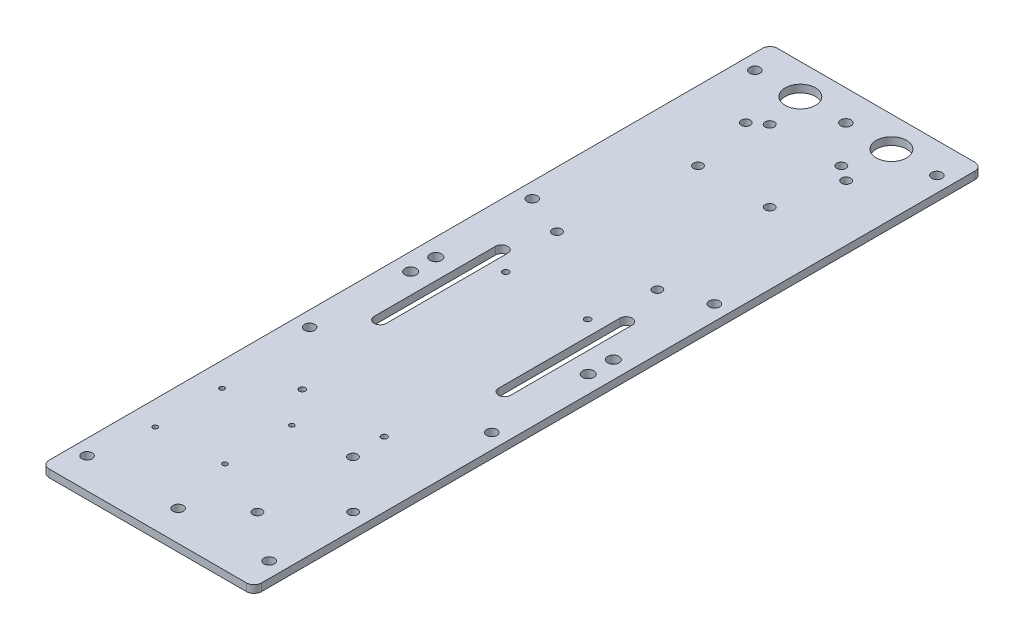
SolidWorks part; units mm, degrees
ref_plane "Front Plane" through (0, 0, 0) normal (0, 0, 1) x (1, 0, 0)
ref_plane "Top Plane" through (0, 0, 0) normal (0, 1, 0) x (1, 0, 0)
ref_plane "Right Plane" through (0, 0, 0) normal (1, 0, 0) x (0, 0, -1)
sketch "Sketch2" plane through (0, 0, 0) normal (0, 1, 0) x (1, 0, 0)
  line L0 (-44.45, 0) -> (44.45, 0) construction
  line L1 (-41.275, 152.4) -> (41.275, 152.4)
  line L2 (-44.45, 149.225) -> (-44.45, -149.225)
  line L3 (-41.275, -152.4) -> (41.275, -152.4)
  line L4 (44.45, 149.225) -> (44.45, -149.225)
  line L5 (0, 152.4) -> (0, -152.4) construction
  arc A0 (-44.45, -149.225) -> (-41.275, -152.4) centre (-41.275, -149.225) ccw
  arc A1 (41.275, -152.4) -> (44.45, -149.225) centre (41.275, -149.225) ccw
  arc A2 (41.275, 152.4) -> (44.45, 149.225) centre (41.275, 149.225) cw
  arc A3 (-41.275, 152.4) -> (-44.45, 149.225) centre (-41.275, 149.225) ccw
  point P8 (0, 0)
  point P13 (-44.45, -152.4)
  point P16 (44.45, -152.4)
  point P21 (-44.45, 152.4)
  dimension "D3" = 3.175
  dimension "D1" = 304.8
  dimension "D2" = 88.9
extrude "Plate Thickness" add sketch "Sketch2" along normal blind 3.175 contours L2 A0 L3 A1 L4 A2 L1 A3
sketch "Sketch3" plane through (0, 3.175, 0) normal (0, 1, 0) x (1, 0, 0)
  line L0 (-44.45, 149.225) -> (-44.45, -149.225) construction
  line L1 (-41.275, 152.4) -> (41.275, 152.4) construction
  line L4 (0, 152.4) -> (0, -152.4) construction
  line L5 (-41.275, -152.4) -> (41.275, -152.4) construction
  line L6 (-41.275, -152.4) -> (41.275, -152.4) construction
  circle A0 centre (-38.1, 139.7) radius 2.159
  circle A1 centre (-38.1, 46.5667) radius 2.159
  circle A2 centre (-38.1, -46.5667) radius 2.159
  circle A3 centre (-38.1, -139.7) radius 2.159
  circle A4 centre (38.1, -139.7) radius 2.159
  circle A5 centre (38.1, -46.5667) radius 2.159
  circle A6 centre (38.1, 46.5667) radius 2.159
  circle A7 centre (38.1, 139.7) radius 2.159
  circle A8 centre (0, 139.7) radius 2.159
  circle A9 centre (0, -139.7) radius 2.159
  dimension "D1" = 4.318
  dimension "D4" = 4.318
  dimension "D2" = 6.35
  dimension "D3" = 12.7
  dimension "D5" = 12.7
  dimension "D6" = 12.7
  dimension "D7" = 93.1333
  dimension "D8" = 93.1333
extrude "Mounting holes" cut sketch "Sketch3" against normal through all
sketch "Sketch4" plane through (0, 3.175, 0) normal (0, 1, 0) x (1, 0, 0)
  line L0 (-21.0058, 39.8143) -> (21.0058, 39.8143) construction
  line L1 (0, 0) -> (0, 139.7) construction
  circle A0 centre (-21.0058, 118.8083) radius 1.905
  circle A1 centre (-21.0058, 39.8143) radius 1.905
  circle A2 centre (21.0058, 39.8143) radius 1.905
  circle A3 centre (21.0058, 118.8083) radius 1.905
  point P13 (0, 39.8143)
  point P17 (0, 69.85)
  point P18 (0, 69.85)
  dimension "D1" = 3.81
  dimension "D2" = 78.994
  dimension "D3" = 42.0116
extrude "Jetson Holes (w/o mount)" cut sketch "Sketch4" against normal through all
sketch "Sketch5" plane through (0, 3.175, 0) normal (0, 1, 0) x (1, 0, 0)
  line L0 (-41.275, 152.4) -> (41.275, 152.4) construction
  line L1 (44.45, 149.225) -> (44.45, -149.225) construction
  circle A1 centre (-15.3784, 123.19) radius 1.905
  circle A3 centre (14.619, 123.19) radius 1.905
  circle A4 centre (14.619, 93.1926) radius 1.905
  circle A5 centre (-15.3784, 93.1926) radius 1.905
  dimension "D1" = 3.81
  dimension "D2" = 29.9974
  dimension "D4" = 29.21
  dimension "D5" = 29.831
  dimension "D3" = 29.9974
extrude "PDB holes" cut sketch "Sketch5" against normal through all
sketch "Sketch6" plane through (0, 3.175, 0) normal (0, 1, 0) x (1, 0, 0)
  line L0 (-41.275, -152.4) -> (41.275, -152.4) construction
  circle A6 centre (37.9175, -104.394) radius 1.905
  circle A7 centre (17.9175, -84.46) radius 1.905
  circle A8 centre (17.9175, -124.46) radius 1.905
  dimension "D1" = 27.94
  dimension "D5" = 3.81
  dimension "D6" = 40
  dimension "D7" = 20
  dimension "D8" = 20.066
sketch "Sketch7" plane through (0, 3.175, 0) normal (0, 1, 0) x (1, 0, 0)
  line L0 (0, 152.4) -> (0, -152.4) construction
  line L1 (-41.275, 152.4) -> (41.275, 152.4) construction
  line L2 (-41.275, -152.4) -> (41.275, -152.4) construction
  line L3 (17.145, 14.4893) -> (-17.145, 14.4893) construction
  circle A0 centre (-17.145, 14.4893) radius 1.27
  circle A1 centre (-17.145, -70.6007) radius 1.27
  circle A2 centre (17.145, -70.6007) radius 1.27
  circle A3 centre (17.145, 14.4893) radius 1.27
  point P14 (0, 14.4893)
  dimension "D1" = 2.54
  dimension "D2" = 85.09
  dimension "D3" = 34.29
extrude "PixHawk Holes" cut sketch "Sketch7" against normal through all
sketch "Sketch8" plane through (0, 3.175, 0) normal (0, 1, 0) x (1, 0, 0)
  line L0 (0, 152.4) -> (0, -115.5095) construction
  line L1 (-41.275, 152.4) -> (41.275, 152.4) construction
  line L2 (-26.035, 21.6897) -> (-26.035, -29.1103) construction
  line L3 (-23.495, 21.6897) -> (-23.495, -29.1103)
  line L4 (-28.575, 21.6897) -> (-28.575, -29.1103)
  line L5 (26.035, 21.6897) -> (26.035, -29.1103) construction
  line L6 (23.495, 21.6897) -> (23.495, -29.1103)
  line L7 (28.575, 21.6897) -> (28.575, -29.1103)
  arc A0 (-23.495, 21.6897) -> (-28.575, 21.6897) centre (-26.035, 21.6897) ccw
  arc A1 (-28.575, -29.1103) -> (-23.495, -29.1103) centre (-26.035, -29.1103) ccw
  arc A2 (23.495, 21.6897) -> (28.575, 21.6897) centre (26.035, 21.6897) cw
  arc A3 (28.575, -29.1103) -> (23.495, -29.1103) centre (26.035, -29.1103) cw
  point P7 (-26.035, -3.7103)
  point P14 (26.035, -3.7103)
  dimension "D1" = 50.8
  dimension "D2" = 5.08
  dimension "D3" = 26.035
extrude "Battery Holes" cut sketch "Sketch8" against normal through all
sketch "Sketch9" plane through (0, 3.175, 0) normal (0, 1, 0) x (1, 0, 0)
  line L0 (44.45, 149.225) -> (44.45, -149.225) construction
  line L1 (-41.275, -152.4) -> (41.275, -152.4) construction
  circle A0 centre (6.8334, -85.3) radius 2
  circle A1 centre (34.3334, -85.3) radius 2
  circle A2 centre (34.3334, -114.3) radius 2
  circle A3 centre (6.8334, -114.3) radius 2
  dimension "D1" = 4
  dimension "D3" = 10.1166
  dimension "D5" = 38.1
  dimension "D2" = 27.5
  dimension "D4" = 29
sketch "Sketch10" plane through (0, 3.175, 0) normal (0, 1, 0) x (1, 0, 0)
  line L0 (-44.45, 149.225) -> (-44.45, -149.225) construction
  circle A0 centre (-34.3155, -87.0086) radius 1
  circle A1 centre (-34.29, -115.0086) radius 1
  circle A2 centre (-6.3166, -85.7891) radius 1
  circle A3 centre (-6.3166, -113.7891) radius 1
  dimension "D1" = 2
  dimension "D2" = 28
  dimension "D3" = 28
  dimension "D4" = 28
  dimension "D5" = 10.16
extrude "Ventral Camera holes" cut sketch "Sketch10" against normal up to next
sketch "Sketch12" plane through (0, 3.175, 0) normal (0, 1, 0) x (1, 0, 0)
  line L0 (-41.275, 152.4) -> (41.275, 152.4) construction
  circle A0 centre (-19.05, 139.7) radius 6.35
  circle A1 centre (19.05, 139.7) radius 6.35
  circle A2 centre (-38.1, 139.7) radius 2.159 construction
  dimension "D1" = 19.05
  dimension "D3" = 12.7
  dimension "D2" = 38.1
  dimension "D4" = 12.7
extrude "Wifi antenna holes" cut sketch "Sketch12" against normal through all
extrude "TeraRanger Holes" cut sketch "Sketch6" against normal through all
sketch "Sketch14" plane through (0, 3.175, 0) normal (0, 1, 0) x (1, 0, 0)
  line L0 (0, 0) -> (106.8092, 0) construction
  line L1 (106.8092, 0) -> (-134.4112, 0) construction
  line L2 (0, 0) -> (0, -162.7051) construction
  circle A0 centre (-37.138, 5.2462) radius 2.3812
  circle A1 centre (-37.138, -5.2462) radius 2.3812
  circle A2 centre (37.138, -5.2462) radius 2.3812
  circle A3 centre (37.138, 5.2462) radius 2.3812
  dimension "D1" = 10.4925
  dimension "D2" = 4.7625
extrude "Sonarholes" cut sketch "Sketch14" against normal through all
